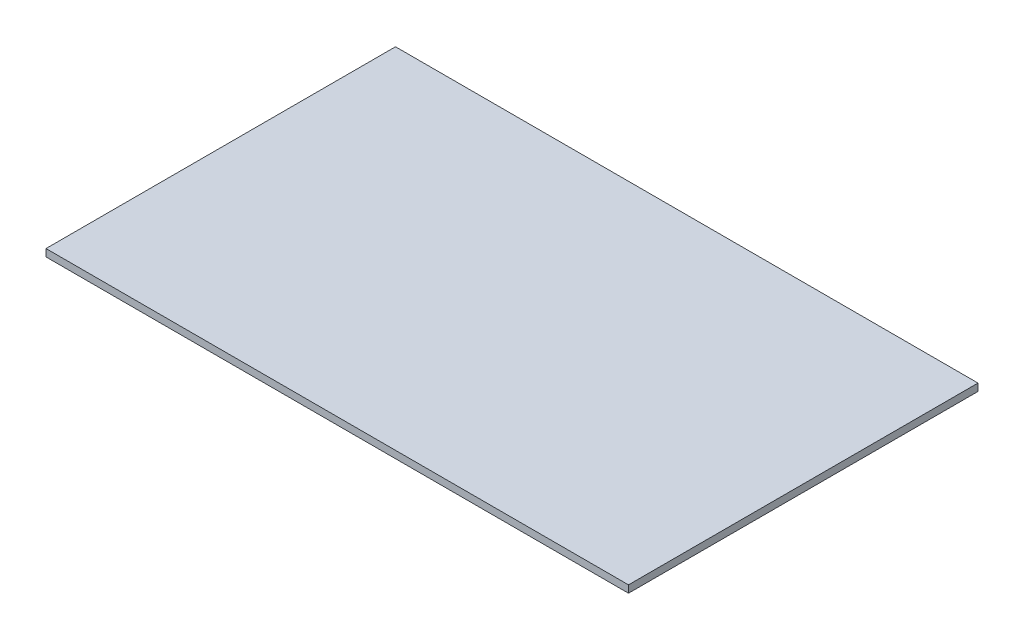
SolidWorks part; units mm, degrees
ref_plane "Front Plane" through (0, 0, 0) normal (0, 0, 1) x (1, 0, 0)
ref_plane "Top Plane" through (0, 0, 0) normal (0, 1, 0) x (1, 0, 0)
ref_plane "Right Plane" through (0, 0, 0) normal (1, 0, 0) x (0, 0, -1)
sketch "Sketch1" plane through (0, 0, 0) normal (0, 1, 0) x (1, 0, 0)
  line L1 (-51.4865, 36.6126) -> (75.5135, 36.6126)
  line L2 (-51.4865, 36.6126) -> (-51.4865, -39.5874)
  line L3 (-51.4865, -39.5874) -> (75.5135, -39.5874)
  line L4 (75.5135, 36.6126) -> (75.5135, -39.5874)
  dimension "D1" = 127
  dimension "D2" = 76.2
extrude "Boss-Extrude1" add sketch "Sketch1" along normal blind 1.5875 contours L2 L3 L4 L1
